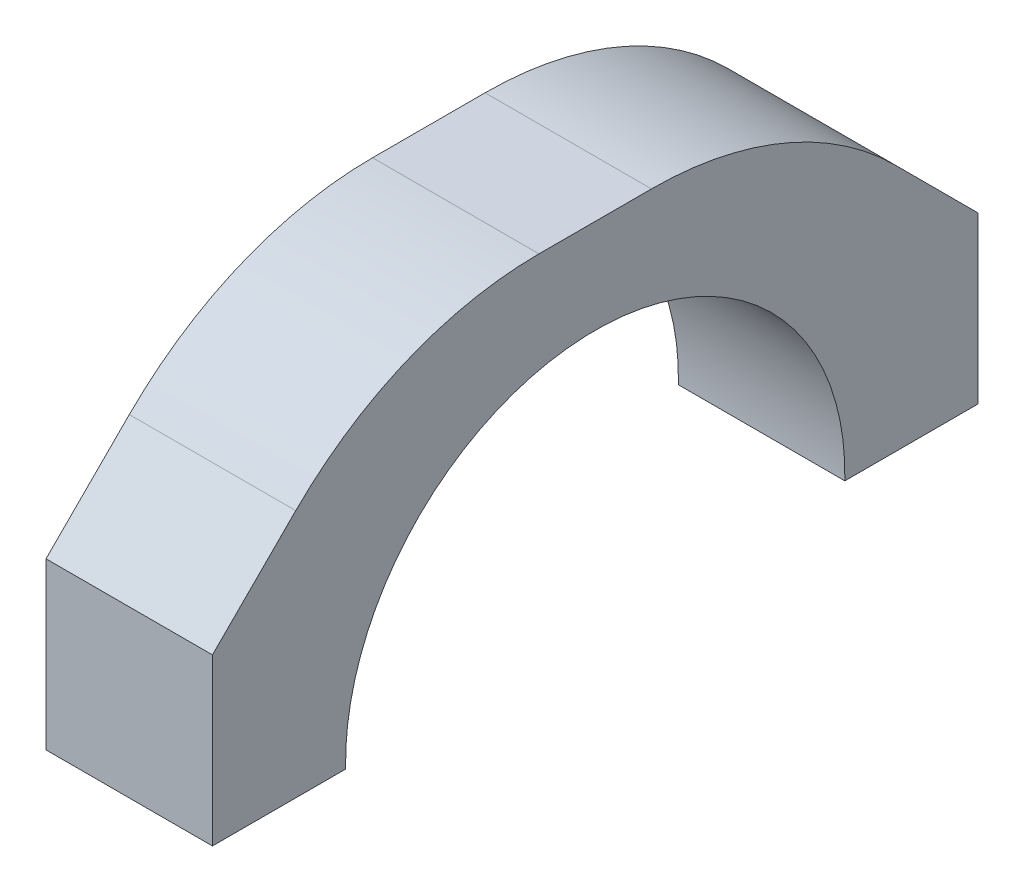
SolidWorks part; units mm, degrees
material "2014 Alloy"
ref_plane "Front Plane" through (0, 0, 0) normal (0, 0, 1) x (1, 0, 0)
ref_plane "Top Plane" through (0, 0, 0) normal (0, 1, 0) x (1, 0, 0)
ref_plane "Right Plane" through (0, 0, 0) normal (1, 0, 0) x (0, 0, -1)
sketch "Sketch1" plane through (0, 0, 0) normal (1, 0, 0) x (0, 0, -1)
  line L0 (-33.4947, 0) -> (33.4947, 0)
  line L1 (33.4947, 0) -> (33.4947, -29.5)
  line L2 (33.4947, -29.5) -> (23.4947, -29.5)
  line L3 (0, 0) -> (0, -30) construction
  line L4 (-33.4947, -29.5) -> (-23.4947, -29.5)
  line L5 (-33.4947, 0) -> (-33.4947, -29.5)
  arc A0 (23.4947, -29.5) -> (-23.4947, -29.5) centre (0, -30) ccw
  dimension "D1" = 30
  dimension "D3" = 23.5
  dimension "D2" = 10
  dimension "D4" = 0.5
extrude "Boss-Extrude1" add sketch "Sketch1" along normal blind 12
chamfer "Chamfer1" distance 16 angle 45 2 edges at (6, 0, -33.4947) (6, 0, 33.4947)
fillet "Fillet1" radius 30 2 edges at (6, 0, -17.4947) (6, 0, 17.4947)
hole_wizard "M5 Clearance Hole1" [suppressed] positions "Sketch3" profile "Sketch2" hole size "M5" standard "ISO"
sketch "Sketch3" plane through (0, -29.5, 0) normal (0, -1, 0) x (-1, 0, 0)
  line L3 (-6, -23.4947) -> (-6, 23.4947) construction
  line L4 (-12, 23.4947) -> (0, 23.4947) construction
  line L5 (-6, 23.4947) -> (-6, 33.4947) construction
  line L6 (-12, 33.4947) -> (0, 33.4947) construction
  line L7 (-6, -23.4947) -> (-6, -33.4947) construction
  line L8 (-12, -33.4947) -> (0, -33.4947) construction
  point P0 (-6, -28.4947)
  point P2 (-6, 28.4947)
sketch "Sketch2" plane through (6, -29.5, 28.4947) normal (1, 0, 0) x (0, 0, -1)
  line L0 (0, 0) -> (0, 29.5)
  line L1 (0, 29.5) -> (2.75, 29.5)
  line L2 (2.75, 29.5) -> (2.75, 0)
  line L5 (2.75, 0) -> (0, 0)
  line L11 (0, -6.35) -> (0, 107.95) construction
  dimension "Thru Hole Dia." = 5.5
  dimension "Thru Hole Depth" = 29.5
sketch "Sketch4" [suppressed] plane through (0, 0, 0) normal (0, 1, 0) x (1, 0, 0)
  circle A0 centre (6, -28.4947) radius 5.5
  circle A1 centre (6, 28.4947) radius 5.5
  dimension "D1" = 11
extrude "Cut-Extrude1" [suppressed] cut sketch "Sketch4" against normal blind 16
sketch "Sketch5" plane through (12, 0, 0) normal (1, 0, 0) x (0, 0, -1)
  line L0 (-33.4947, -19.2223) -> (-33.4947, -6.0171)
  line L1 (-33.4947, -19.2223) -> (-23.0911, -19.2223)
  line L2 (-33.4947, -6.0171) -> (-23.0911, -6.0171)
  line L3 (-23.0911, -19.2223) -> (-23.0911, -6.0171)
  line L4 (-33.4947, -19.2223) -> (-23.0911, -6.0171) construction
  line L5 (-33.4947, -6.0171) -> (-23.0911, -19.2223) construction
  line L6 (-33.4947, -16) -> (-33.4947, -29.5) construction
  line L7 (0, 0) -> (0, -19.2223) construction
  line L8 (5.0683, 0) -> (-5.0683, 0) construction
  line L9 (33.4947, -6.0171) -> (23.0911, -19.2223) construction
  line L10 (33.4947, -19.2223) -> (23.0911, -6.0171) construction
  line L11 (23.0911, -19.2223) -> (23.0911, -6.0171)
  line L12 (33.4947, -6.0171) -> (23.0911, -6.0171)
  line L13 (33.4947, -19.2223) -> (23.0911, -19.2223)
  line L14 (33.4947, -19.2223) -> (33.4947, -6.0171)
  arc A0 (-5.0683, 0) -> (-26.2815, -8.7868) centre (-5.0683, -30) ccw construction
  point P1 (-28.2929, -12.6197)
  point P3 (-23.0911, -5.6272)
  point P19 (23.0911, -5.6272)
  point P20 (28.2929, -12.6197)
extrude "Boss-Extrude2" [suppressed] add sketch "Sketch5" against normal blind 12
sketch "Sketch6" plane through (12, 0, 0) normal (1, 0, 0) x (0, 0, -1)
  line L0 (34.4947, -15.5858) -> (26.9886, -8.0797)
  line L1 (5.0683, 1) -> (-5.0683, 1)
  line L2 (-26.9886, -8.0797) -> (-34.4947, -15.5858)
  line L3 (-34.4947, -15.5858) -> (-34.4947, -30.5)
  line L4 (-34.4947, -30.5) -> (-22.4944, -30.5)
  line L5 (22.4944, -30.5) -> (34.4947, -30.5)
  line L6 (34.4947, -30.5) -> (34.4947, -15.5858)
  line L7 (33.4947, -16) -> (26.2815, -8.7868)
  line L8 (5.0683, 0) -> (-5.0683, 0)
  line L9 (-26.2815, -8.7868) -> (-33.4947, -16)
  line L10 (-33.4947, -16) -> (-33.4947, -29.5)
  line L11 (-33.4947, -29.5) -> (-23.4947, -29.5)
  line L12 (23.4947, -29.5) -> (33.4947, -29.5)
  line L13 (33.4947, -29.5) -> (33.4947, -16)
  line L14 (33.4947, -16) -> (26.2815, -8.7868) construction
  line L15 (5.0683, 0) -> (-5.0683, 0) construction
  line L16 (-26.2815, -8.7868) -> (-33.4947, -16) construction
  line L17 (-33.4947, -16) -> (-33.4947, -29.5) construction
  line L18 (-33.4947, -29.5) -> (-23.4947, -29.5) construction
  line L19 (23.4947, -29.5) -> (33.4947, -29.5) construction
  line L20 (33.4947, -29.5) -> (33.4947, -16) construction
  arc A0 (26.9886, -8.0797) -> (5.0683, 1) centre (5.0683, -30) ccw
  arc A1 (-5.0683, 1) -> (-26.9886, -8.0797) centre (-5.0683, -30) ccw
  arc A2 (22.4944, -30.5) -> (-22.4944, -30.5) centre (0, -30) ccw
  arc A3 (26.2815, -8.7868) -> (5.0683, 0) centre (5.0683, -30) ccw
  arc A4 (-5.0683, 0) -> (-26.2815, -8.7868) centre (-5.0683, -30) ccw
  arc A5 (23.4947, -29.5) -> (-23.4947, -29.5) centre (0, -30) ccw
  arc A6 (26.2815, -8.7868) -> (5.0683, 0) centre (5.0683, -30) ccw construction
  arc A7 (-5.0683, 0) -> (-26.2815, -8.7868) centre (-5.0683, -30) ccw construction
  arc A8 (23.4947, -29.5) -> (-23.4947, -29.5) centre (0, -30) ccw construction
  dimension "D1" = 0
  dimension "D2" = 1
extrude "Boss-Extrude3" add sketch "Sketch6" against normal blind 15
